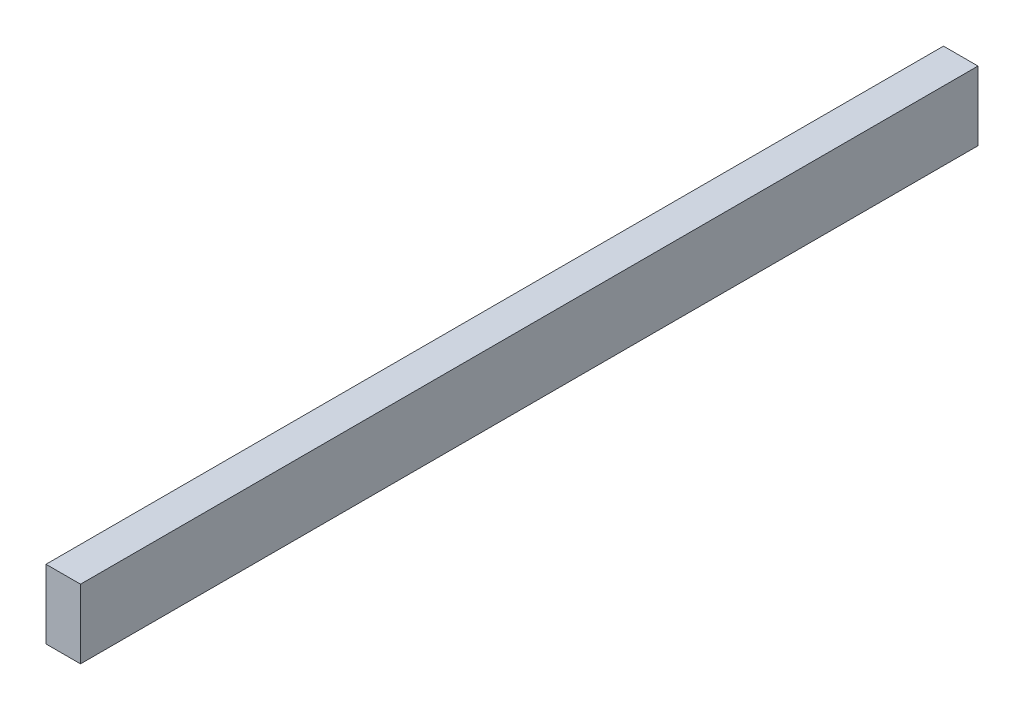
SolidWorks part; units mm, degrees
ref_plane "Front Plane" through (0, 0, 0) normal (0, 0, 1) x (1, 0, 0)
ref_plane "Top Plane" through (0, 0, 0) normal (0, 1, 0) x (1, 0, 0)
ref_plane "Right Plane" through (0, 0, 0) normal (1, 0, 0) x (0, 0, -1)
sketch "Sketch1" plane through (0, 0, 0) normal (0, 1, 0) x (1, 0, 0)
  line L1 (0, 0) -> (25.4, 0)
  line L2 (0, 0) -> (0, 660.4)
  line L3 (0, 660.4) -> (25.4, 660.4)
  line L4 (25.4, 0) -> (25.4, 660.4)
  dimension "D1" = 660.4
  dimension "D2" = 25.4
extrude "Boss-Extrude1" add sketch "Sketch1" along normal blind 50.8
